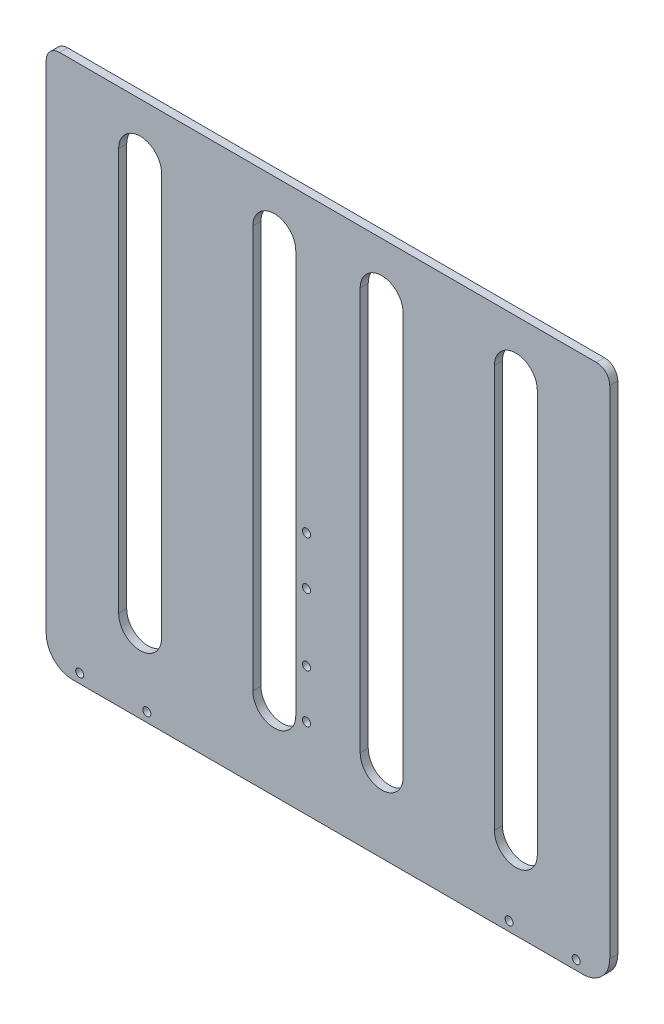
SolidWorks part; units mm, degrees
material "A-玻璃纤维"
ref_plane "前视基准面" through (0, 0, 0) normal (0, 0, 1) x (1, 0, 0)
ref_plane "上视基准面" through (0, 0, 0) normal (0, 1, 0) x (1, 0, 0)
ref_plane "右视基准面" through (0, 0, 0) normal (1, 0, 0) x (0, 0, -1)
sketch "草图1" plane through (0, 0, 0) normal (0, 0, 1) x (1, 0, 0)
  line L1 (0, 0) -> (210, 0)
  line L2 (0, 0) -> (0, 200)
  line L3 (0, 200) -> (210, 200)
  line L4 (210, 0) -> (210, 200)
  dimension "D1" = 210
  dimension "D2" = 200
extrude "凸台-拉伸1" add sketch "草图1" along normal blind 3
sketch "草图2" plane through (0, 0, 3) normal (0, 0, 1) x (1, 0, 0)
  line L0 (105, 200) -> (105, 0) construction
  line L1 (210, 200) -> (0, 200) construction
  line L2 (0, 0) -> (210, 0) construction
  line L3 (35, 180) -> (35, 30) construction
  line L4 (43, 180) -> (43, 30)
  line L5 (27, 180) -> (27, 30)
  line L6 (175, 180) -> (175, 30) construction
  line L7 (167, 180) -> (167, 30)
  line L8 (183, 180) -> (183, 30)
  line L9 (85, 180) -> (85, 30) construction
  line L10 (93, 180) -> (93, 30)
  line L11 (77, 180) -> (77, 30)
  line L12 (125, 180) -> (125, 30) construction
  line L13 (117, 180) -> (117, 30)
  line L14 (133, 180) -> (133, 30)
  arc A0 (43, 180) -> (27, 180) centre (35, 180) ccw
  arc A1 (27, 30) -> (43, 30) centre (35, 30) ccw
  arc A2 (167, 180) -> (183, 180) centre (175, 180) cw
  arc A3 (183, 30) -> (167, 30) centre (175, 30) cw
  arc A4 (93, 180) -> (77, 180) centre (85, 180) ccw
  arc A5 (77, 30) -> (93, 30) centre (85, 30) ccw
  arc A6 (117, 180) -> (133, 180) centre (125, 180) cw
  arc A7 (133, 30) -> (117, 30) centre (125, 30) cw
  point P8 (35, 105)
  point P16 (175, 105)
  point P22 (85, 105)
  point P30 (125, 105)
  dimension "D2" = 8
  dimension "D5" = 20
  dimension "D1" = 70
  dimension "D3" = 20
  dimension "D4" = 150
extrude "切除-拉伸1" cut sketch "草图2" against normal through all
fillet "圆角2" radius 10 2 edges at (0, 0, 1.5) (210, 0, 1.5)
fillet "圆角3" radius 5 2 edges at (210, 200, 1.5) (0, 200, 1.5)
sketch "草图4" plane through (0, 0, 3) normal (0, 0, 1) x (1, 0, 0)
  line L0 (12.5, 3.5) -> (37.5, 3.5) construction
  line L1 (105, 200) -> (105, 0) construction
  line L2 (205, 200) -> (5, 200) construction
  line L3 (10, 0) -> (200, 0) construction
  line L4 (197.5, 3.5) -> (172.5, 3.5) construction
  circle A0 centre (12.5, 3.5) radius 1.5
  circle A2 centre (37.5, 3.5) radius 1.5
  circle A6 centre (172.5, 3.5) radius 1.5
  circle A8 centre (197.5, 3.5) radius 1.5
  point P11 (105, 200)
  point P16 (105, 0)
  dimension "D6" = 3
  dimension "D1" = 160
  dimension "D2" = 25
  dimension "D5" = 3.5
extrude "切除-拉伸2" cut sketch "草图4" against normal through all and the other way through all
sketch "草图5" plane through (0, 0, 3) normal (0, 0, 1) x (1, 0, 0)
  line L0 (97, 200) -> (97, 0) construction
  line L1 (205, 200) -> (5, 200) construction
  line L2 (10, 0) -> (200, 0) construction
  line L3 (93, 30) -> (93, 180) construction
  circle A0 centre (97, 48) radius 1.5
  circle A1 centre (97, 30) radius 1.5
  circle A2 centre (97, 73) radius 1.5
  circle A3 centre (97, 91) radius 1.5
  dimension "D2" = 18
  dimension "D3" = 3
  dimension "D4" = 18
  dimension "D1" = 4
  dimension "D5" = 25
  dimension "D6" = 30
extrude "切除-拉伸3" cut sketch "草图5" against normal through all
